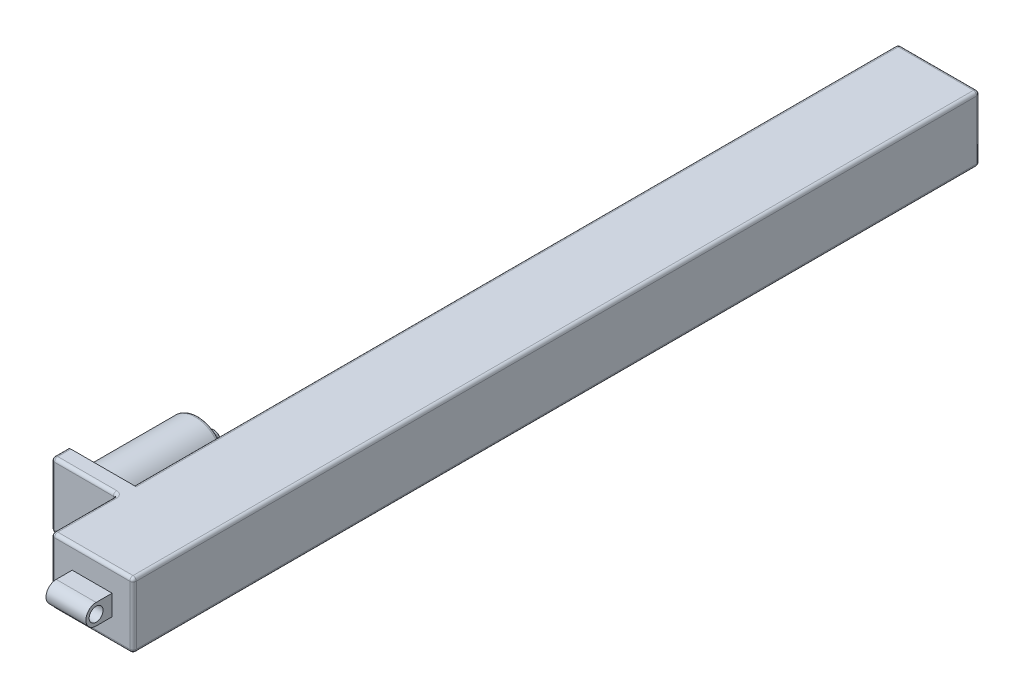
SolidWorks part; units mm, degrees
ref_plane "Front Plane" through (0, 0, 0) normal (0, 0, 1) x (1, 0, 0)
ref_plane "Top Plane" through (0, 0, 0) normal (0, 1, 0) x (1, 0, 0)
ref_plane "Right Plane" through (0, 0, 0) normal (1, 0, 0) x (0, 0, -1)
sketch "Sketch1" plane through (0, 0, 0) normal (0, 0, 1) x (1, 0, 0)
  line L1 (-12.5, -10) -> (12.5, -10)
  line L2 (-12.5, -10) -> (-12.5, 10)
  line L3 (-12.5, 10) -> (12.5, 10)
  line L4 (12.5, -10) -> (12.5, 10)
  line L5 (-12.5, -10) -> (12.5, 10) construction
  line L6 (-12.5, 10) -> (12.5, -10) construction
  circle A0 centre (0, 0) radius 4
  point P0 (0, 0)
  dimension "D3" = 8
  dimension "D1" = 25
  dimension "D2" = 20
extrude "Boss-Extrude1" add sketch "Sketch1" along normal blind 254
sketch "Sketch2" plane through (0, 0, 254) normal (0, 0, 1) x (1, 0, 0)
  line L1 (-12.5, -10) -> (12.5, -10)
  line L2 (-12.5, -10) -> (-12.5, 10)
  line L3 (-12.5, 10) -> (12.5, 10)
  line L4 (12.5, -10) -> (12.5, 10)
  line L5 (-12.5, -10) -> (12.5, 10) construction
  line L6 (-12.5, 10) -> (12.5, -10) construction
  point P0 (0, 0)
extrude "Boss-Extrude2" add sketch "Sketch2" along normal blind 5
sketch "Sketch6" plane through (0, 0, 0) normal (1, 0, 0) x (0, 0, -1)
  line L0 (-259, -3.125) -> (-259, 3.125)
  line L1 (-259, -10) -> (-259, 10) construction
  line L2 (-259, 10) -> (-259, -10)
  line L3 (-256.7181, 0) -> (-264.036, 0) construction
  line L4 (-259, 3.125) -> (-263.8892, 3.125)
  line L5 (-259, -3.125) -> (-263.8892, -3.125)
  arc A0 (-263.8892, 3.125) -> (-263.8892, -3.125) centre (-263.8892, 0) ccw
  circle A1 centre (-263.8892, 0) radius 2.125
  point P5 (-259, 0)
  dimension "D4" = 4.25
  dimension "D5" = 1
  dimension "D1" = 6.25
  dimension "D2" = 0
  dimension "D3" = 4.8892
extrude "Boss-Extrude3" add sketch "Sketch6" along normal up to surface and the other way up to surface
sketch "Sketch7" plane through (-12.5, 0, 0) normal (-1, 0, 0) x (0, 0, 1)
  line L0 (239, 10) -> (239, -10)
  line L1 (259, 10) -> (0, 10) construction
  line L2 (259, -10) -> (0, -10) construction
  line L3 (259, 10) -> (259, 3.125) construction
  line L5 (239, 10) -> (234, 10)
  line L6 (239, 10) -> (239, -10)
  line L7 (239, -10) -> (234, -10)
  line L8 (234, 10) -> (234, -10)
  line M4 (0, -10) -> (259, -10)
  line M10 (259, 10) -> (0, 10)
  dimension "D1" = 20
  dimension "D2" = 5
extrude "Boss-Extrude4" add sketch "Sketch7" along normal blind 20 contours L8 L0 M10 M4
sketch "Sketch8" plane through (0, 0, 234) normal (0, 0, -1) x (-1, 0, 0)
  circle A0 centre (22.5, 0) radius 8.5
  dimension "D1" = 17
extrude "Boss-Extrude5" add sketch "Sketch8" along normal blind 30
sketch "Sketch9" plane through (0, 0, 204) normal (0, 0, -1) x (-1, 0, 0)
  circle A0 centre (22.5, 0) radius 2.5
  dimension "D1" = 5
extrude "Boss-Extrude6" add sketch "Sketch9" along normal blind 5
fillet "Fillet1" radius 1 12 edges at (-22.5, 10, 239) (-32.5, 0, 239) (-22.5, -10, 239) (-32.5, 10, 236.5) (-32.5, -10, 236.5) (-12.5, 0, 239) (-14, 0, 234) (-31, 0, 204) (-25, 0, 204) (-25, 0, 199) (-12.5, -10, 249) (-12.5, 10, 249)
fillet "Fillet2" radius 1 17 edges at (-12.5, -6.0625, 259) (-12.2071, -9.7071, 259) (-12.5, 6.0625, 259) (-12.2071, 9.7071, 259) (4, 0, 0) (0, 10, 0) (-12.5, 0, 0) (0, -10, 0) (12.5, 0, 0) (12.5, 6.5625, 259) (12.5, -6.5625, 259) (0.5, -10, 259) (0.5, 10, 259) (-12.5, 10, 117) (-12.5, -10, 117) (12.5, -10, 129.5) (12.5, 10, 129.5)
sketch "Sketch10" plane through (0, -3.125, 0) normal (0, -1, 0) x (1, 0, 0)
  line L1 (-8.5707, 289.6321) -> (3.6293, 289.6321)
  line L12 (-6.1, 273.9939) -> (-12.9201, 273.9939)
  line L13 (-12.9201, 273.9939) -> (-12.9201, 258.124)
  line L14 (-12.9201, 258.124) -> (-12.5, 258)
  line L15 (-11.5, 259) -> (-6.1, 259)
  line L16 (11.5, 259) -> (6.1, 259)
  line L17 (12.9201, 258.124) -> (12.5, 258)
  line L18 (12.9201, 273.9939) -> (12.9201, 258.124)
  line L19 (6.1, 273.9939) -> (12.9201, 273.9939)
  line L21 (-6.1, 273.9939) -> (-6.1, 259)
  line L22 (6.1, 273.9939) -> (6.1, 259)
  arc A0 (-12.5, 258) -> (-11.5, 259) centre (-11.5, 258) cw
  arc A1 (12.5, 258) -> (11.5, 259) centre (11.5, 258) ccw
  point P0 (-2.4707, 274.316)
  point P25 (0, 273.9939)
extrude "Cut-Extrude1" cut sketch "Sketch10" against normal blind 10
